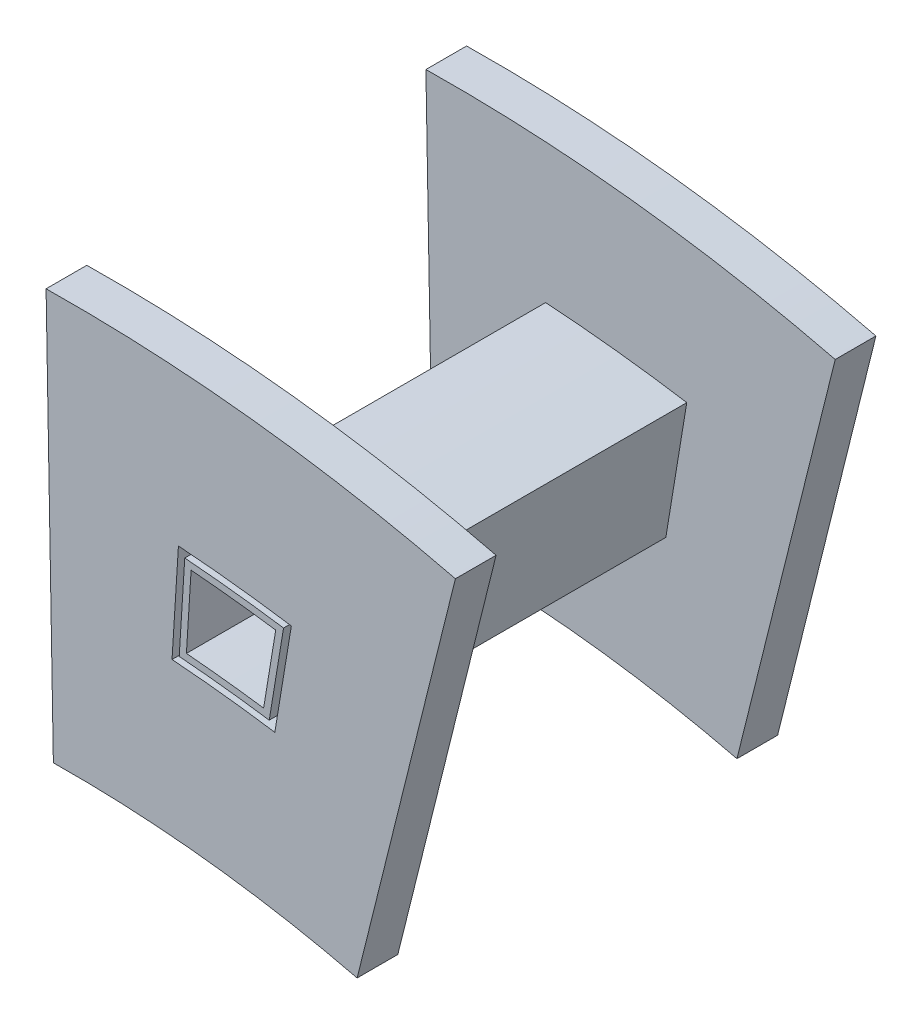
SolidWorks part; units mm, degrees
ref_plane "Front Plane" through (0, 0, 0) normal (0, 0, 1) x (1, 0, 0)
ref_plane "Top Plane" through (0, 0, 0) normal (0, 1, 0) x (1, 0, 0)
ref_plane "Right Plane" through (0, 0, 0) normal (1, 0, 0) x (0, 0, -1)
sketch "Sketch1" plane through (0, 0, 16.743) normal (0, 0, 1) x (1, 0, 0)
  line L2 (-4.1063, -35.6842) -> (-7.2155, 138.0157) construction
  line L3 (-5.7709, 84.3039) -> (-5.2339, 54.3087)
  line L5 (8.1565, 72.3722) -> (-4.1063, -35.6842) construction
  line L6 (-20.2284, 71.8641) -> (-4.1063, -35.6842) construction
  line L7 (24.4034, 80.8796) -> (17.1587, 51.7675)
  line L8 (12.3094, 71.8197) -> (11.0921, 64.4186) construction
  line L9 (3.9854, 72.7643) -> (3.5133, 65.2787) construction
  line L10 (12.3094, 71.8197) -> (11.0921, 64.4186)
  line L11 (3.9854, 72.7643) -> (3.5133, 65.2787)
  arc A2 (17.1587, 51.7675) -> (-5.2339, 54.3087) centre (-4.1063, -35.6842) ccw
  arc A3 (12.3094, 71.8197) -> (3.9854, 72.7643) centre (-4.1063, -35.6842) ccw construction
  arc A4 (-16.074, 72.4053) -> (-24.3588, 71.1633) centre (-4.1063, -35.6842) ccw construction
  arc A5 (24.4034, 80.8796) -> (-5.7709, 84.3039) centre (-4.1063, -35.6842) ccw
  arc A6 (11.0921, 64.4186) -> (3.5133, 65.2787) centre (-4.1063, -35.6842) ccw construction
  arc A7 (12.3094, 71.8197) -> (3.9854, 72.7643) centre (-4.1063, -35.6842) ccw
  arc A8 (11.0921, 64.4186) -> (3.5133, 65.2787) centre (-4.1063, -35.6842) ccw
  point P109 (0, 0)
  dimension "D1" = 90
  dimension "D2" = 7.5
  dimension "D3" = 15
  dimension "D5" = 7.5005
  dimension "D8" = 119.9997
  dimension "D4" = 165
  dimension "D6" = 30
  dimension "D7" = 8.3774
extrude "Boss-Extrude1" add sketch "Sketch1" along normal blind 3 from offset 0.1
sketch "Sketch2" plane through (0, 0, 19.843) normal (0, 0, 1) x (1, 0, 0)
  line L0 (3.9854, 72.7643) -> (3.5133, 65.2787) construction
  line L1 (11.0921, 64.4186) -> (12.3094, 71.8197) construction
  line L2 (3.9854, 72.7643) -> (3.5133, 65.2787)
  line L3 (11.0921, 64.4186) -> (12.3094, 71.8197)
  arc A0 (11.0921, 64.4186) -> (3.5133, 65.2787) centre (-4.1063, -35.6842) ccw construction
  arc A1 (12.3094, 71.8197) -> (3.9854, 72.7643) centre (-4.1063, -35.6842) ccw construction
  arc A2 (11.0921, 64.4186) -> (3.5133, 65.2787) centre (-4.1063, -35.6842) ccw
  arc A3 (12.3094, 71.8197) -> (3.9854, 72.7643) centre (-4.1063, -35.6842) ccw
extrude "Extrude-Thin1" add sketch "Sketch2" along normal blind 25 separate body thin
sketch "Sketch3" plane through (0, 0, 44.843) normal (0, 0, 1) x (1, 0, 0)
  line L1 (11.0921, 64.4186) -> (12.3094, 71.8197) construction
  line L2 (-5.7709, 84.3039) -> (-5.2339, 54.3087)
  line L3 (17.1587, 51.7675) -> (24.4034, 80.8796)
  line L4 (-5.7709, 84.3039) -> (-5.2339, 54.3087)
  line L5 (17.1587, 51.7675) -> (24.4034, 80.8796)
  line L6 (3.9854, 72.7643) -> (3.5133, 65.2787) construction
  line L7 (11.0921, 64.4186) -> (12.3094, 71.8197)
  line L8 (3.9854, 72.7643) -> (3.5133, 65.2787)
  arc A1 (12.3094, 71.8197) -> (3.9854, 72.7643) centre (-4.1063, -35.6842) ccw construction
  arc A2 (24.4034, 80.8796) -> (-5.7709, 84.3039) centre (-4.1063, -35.6842) ccw
  arc A3 (17.1587, 51.7675) -> (-5.2339, 54.3087) centre (-4.1063, -35.6842) ccw
  arc A4 (24.4034, 80.8796) -> (-5.7709, 84.3039) centre (-4.1063, -35.6842) ccw
  arc A5 (17.1587, 51.7675) -> (-5.2339, 54.3087) centre (-4.1063, -35.6842) ccw
  arc A6 (11.0921, 64.4186) -> (3.5133, 65.2787) centre (-4.1063, -35.6842) ccw construction
  arc A7 (12.3094, 71.8197) -> (3.9854, 72.7643) centre (-4.1063, -35.6842) ccw
  arc A8 (11.0921, 64.4186) -> (3.5133, 65.2787) centre (-4.1063, -35.6842) ccw
  dimension "D1" = 0
extrude "Boss-Extrude2" add sketch "Sketch3" along normal blind 3 separate body
sketch "Sketch4" plane through (0, 0, 19.843) normal (0, 0, -1) x (-1, 0, 0)
  line L0 (-3.9854, 72.7643) -> (-3.5133, 65.2787) construction
  line L1 (-11.0921, 64.4186) -> (-12.3094, 71.8197) construction
  line L4 (-4.5732, 66.1967) -> (-4.9195, 71.6871)
  line L5 (-11.1577, 70.9792) -> (-10.2649, 65.5508)
  line L6 (-4.5732, 66.1967) -> (-4.9195, 71.6871)
  line L7 (-11.1577, 70.9792) -> (-10.2649, 65.5508)
  line L8 (-3.9854, 72.7643) -> (-3.5133, 65.2787)
  line L9 (-11.0921, 64.4186) -> (-12.3094, 71.8197)
  arc A0 (-3.5133, 65.2787) -> (-11.0921, 64.4186) centre (4.1063, -35.6842) ccw construction
  arc A1 (-3.9854, 72.7643) -> (-12.3094, 71.8197) centre (4.1063, -35.6842) ccw construction
  arc A4 (-4.5732, 66.1967) -> (-10.2649, 65.5508) centre (4.1063, -35.6842) ccw
  arc A5 (-4.9195, 71.6871) -> (-11.1577, 70.9792) centre (4.1063, -35.6842) ccw
  arc A6 (-4.5732, 66.1967) -> (-10.2649, 65.5508) centre (4.1063, -35.6842) ccw
  arc A7 (-4.9195, 71.6871) -> (-11.1577, 70.9792) centre (4.1063, -35.6842) ccw
  arc A8 (-3.5133, 65.2787) -> (-11.0921, 64.4186) centre (4.1063, -35.6842) ccw
  arc A9 (-3.9854, 72.7643) -> (-12.3094, 71.8197) centre (4.1063, -35.6842) ccw
  dimension "D1" = 1
extrude "Boss-Extrude3" add sketch "Sketch4" against normal up to surface (25 mm away) up to face at (7.7269, 68.5869, 44.843)
sketch "Sketch5" plane through (0, 0, 19.843) normal (0, 0, -1) x (-1, 0, 0)
  line L0 (-4.5732, 66.1967) -> (-4.9195, 71.6871) construction
  line L1 (-11.1577, 70.9792) -> (-10.2649, 65.5508) construction
  line L2 (-4.5732, 66.1967) -> (-4.9195, 71.6871)
  line L3 (-11.1577, 70.9792) -> (-10.2649, 65.5508)
  line L4 (-4.0434, 65.7389) -> (-4.4525, 72.2269)
  line L5 (-11.7338, 71.4006) -> (-10.6786, 64.9859)
  arc A0 (-4.5732, 66.1967) -> (-10.2649, 65.5508) centre (4.1063, -35.6842) ccw construction
  arc A1 (-4.9195, 71.6871) -> (-11.1577, 70.9792) centre (4.1063, -35.6842) ccw construction
  arc A2 (-4.5732, 66.1967) -> (-10.2649, 65.5508) centre (4.1063, -35.6842) ccw
  arc A3 (-4.9195, 71.6871) -> (-11.1577, 70.9792) centre (4.1063, -35.6842) ccw
  arc A4 (-4.4525, 72.2269) -> (-11.7338, 71.4006) centre (4.1063, -35.6842) ccw
  arc A5 (-4.0434, 65.7389) -> (-10.6786, 64.9859) centre (4.1063, -35.6842) ccw
  dimension "D1" = 0.5
extrude "Boss-Extrude4" add sketch "Sketch5" along normal blind 3 and the other way blind 28
